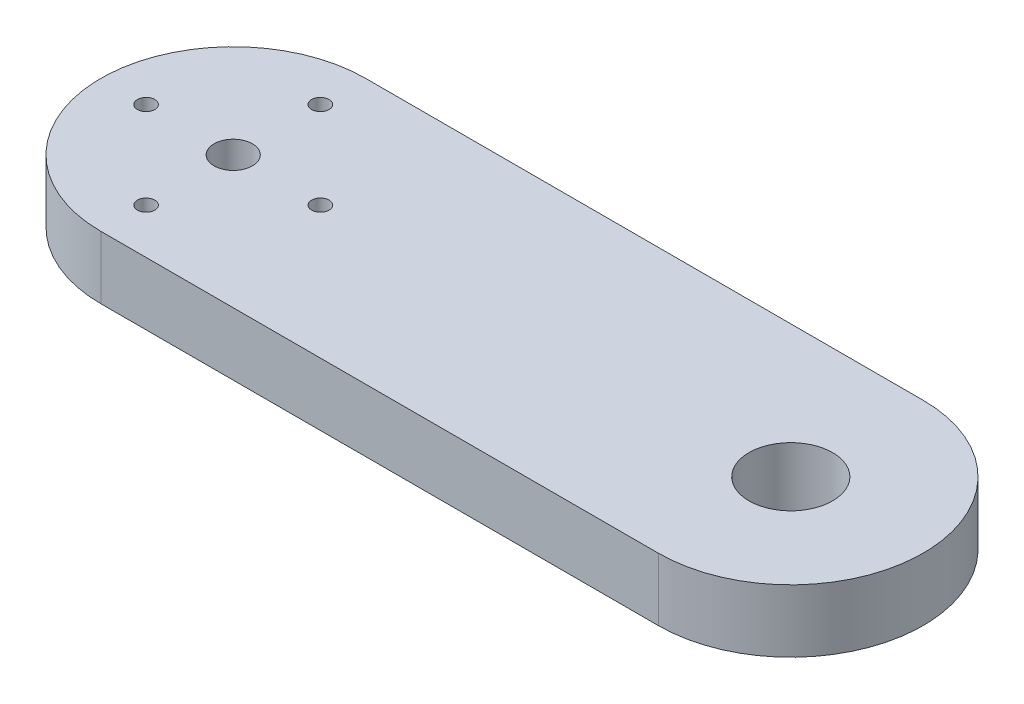
SolidWorks part; units mm, degrees
ref_plane "前视基准面" through (0, 0, 0) normal (0, 0, 1) x (1, 0, 0)
ref_plane "上视基准面" through (0, 0, 0) normal (0, 1, 0) x (1, 0, 0)
ref_plane "右视基准面" through (0, 0, 0) normal (1, 0, 0) x (0, 0, -1)
sketch "草图1" plane through (0, 0, 0) normal (0, 1, 0) x (1, 0, 0)
  line L0 (-2.7557, 0) -> (80, 0) construction
  line L1 (0, 19) -> (80, 19)
  line L2 (0, -19) -> (80, -19)
  line L3 (80, 0) -> (14.4468, 0) construction
  arc A0 (0, 19) -> (0, -19) centre (0, 0) ccw
  arc A1 (80, -19) -> (80, 19) centre (80, 0) ccw
  circle A2 centre (0, 0) radius 2.75
  circle A3 centre (80, 0) radius 6
  circle A4 centre (0, 0) radius 12.5 construction
  point P23 (0, 0)
  dimension "D2" = 12
  dimension "D3" = 19
  dimension "D4" = 5.5
  dimension "D5" = 19
  dimension "D6" = 25
  dimension "D1" = 80
extrude "凸台-拉伸1" add sketch "草图1" along normal blind 9
sketch "草图2" plane through (0, 9, 0) normal (0, 1, 0) x (1, 0, 0)
  circle A0 centre (0, 0) radius 12.5 construction
  circle A1 centre (0, 12.5) radius 1.5
  circle A2 centre (12.5, 0) radius 1.5
  circle A3 centre (0, -12.5) radius 1.5
  circle A4 centre (-12.5, 0) radius 1.5
  point P15 (0, 0)
  dimension "D1" = 25
  dimension "D2" = 3
  dimension "D3" = 4
hole_wizard "M3 螺纹孔的螺纹孔钻头1" positions "3D草图1" profile "草图3" hole size "M3" standard "GB" end condition through all
sketch3d "3D草图1"
  point P0 (0, 9, -12.5)
  point P3 (12.5, 9, 0)
  point P6 (0, 9, 12.5)
  point P9 (-12.5, 9, 0)
sketch "草图3" plane through (0, 9, -12.5) normal (1, 0, 0) x (0, 0, 1)
  line L0 (0, 0) -> (0, 9)
  line L1 (0, 9) -> (1.25, 9)
  line L2 (1.25, 9) -> (1.25, 0)
  line L5 (1.25, 0) -> (0, 0)
  line L11 (0, -6.35) -> (0, 107.95) construction
  dimension "通孔孔直径" = 2.5
  dimension "通孔孔深度" = 9
